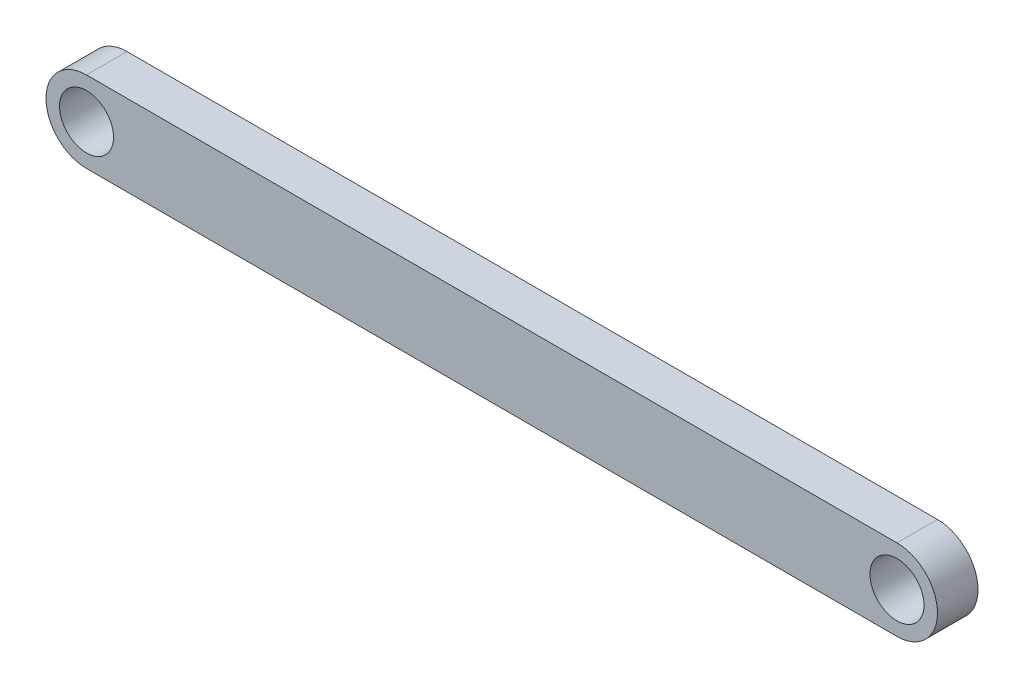
SolidWorks part; units mm, degrees
ref_plane "Front Plane" through (0, 0, 0) normal (0, 0, 1) x (1, 0, 0)
ref_plane "Top Plane" through (0, 0, 0) normal (0, 1, 0) x (1, 0, 0)
ref_plane "Right Plane" through (0, 0, 0) normal (1, 0, 0) x (0, 0, -1)
sketch "Sketch1" plane through (0, 0, 0) normal (0, 0, 1) x (1, 0, 0)
  line L0 (-300, 15) -> (0, 15)
  line L1 (-300, -15) -> (0, -15)
  circle A0 centre (-300, 0) radius 10
  circle A1 centre (0, 0) radius 10
  arc A2 (-300, -15) -> (-300, 15) centre (-300, 0) cw
  arc A3 (0, -15) -> (0, 15) centre (0, 0) ccw
  dimension "D1" = 300
  dimension "D3" = 20
  dimension "D2" = 30
extrude "Extrude1" add sketch "Sketch1" along normal blind 15
